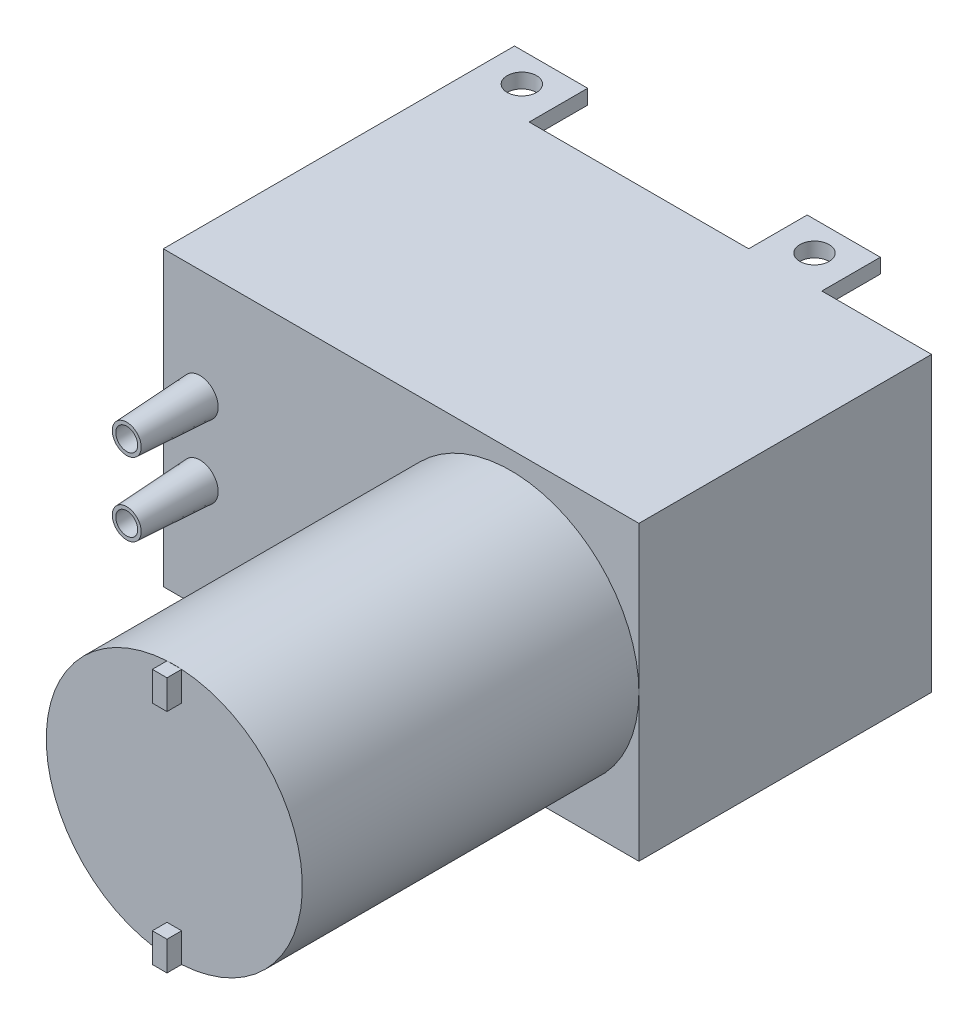
SolidWorks part; units mm, degrees
ref_plane "Plan de face" through (0, 0, 0) normal (0, 0, 1) x (1, 0, 0)
ref_plane "Plan de dessus" through (0, 0, 0) normal (0, 1, 0) x (1, 0, 0)
ref_plane "Plan de droite" through (0, 0, 0) normal (1, 0, 0) x (0, 0, -1)
sketch "Esquisse1" plane through (0, 0, 0) normal (0, 1, 0) x (1, 0, 0)
  line L1 (0, 0) -> (65, 0)
  line L2 (0, 0) -> (0, 40)
  line L3 (0, 40) -> (65, 40)
  line L4 (65, 0) -> (65, 40)
  dimension "D1" = 40
  dimension "D2" = 65
extrude "Boss.-Extru.1" add sketch "Esquisse1" along normal blind 40
sketch "Esquisse2" plane through (0, 0, 0) normal (0, 1, 0) x (1, 0, 0)
  text T0 "Pompe à air"
extrude "Enlèv. mat.-Extru.1" cut sketch "Esquisse2" along normal blind 0.1
sketch "Esquisse3" plane through (0, 0, 0) normal (0, 0, 1) x (1, 0, 0)
  line L0 (47.5, 2.5) -> (47.5, 0) construction
  line L1 (0, 0) -> (65, 0) construction
  line L2 (47.5, 37.5) -> (47.5, 40) construction
  line L3 (0, 40) -> (65, 40) construction
  line L4 (65, 40) -> (65, 0) construction
  circle A0 centre (47.5, 20) radius 17.5
  dimension "D1" = 35
extrude "Boss.-Extru.2" add sketch "Esquisse3" along normal blind 46
sketch "Esquisse4" plane through (0, 0, 46) normal (0, 0, 1) x (1, 0, 0)
  line L0 (65, 20) -> (30, 20) construction
  line L1 (48.5, 2.5286) -> (46.5, 2.5286)
  line L2 (48.5, 2.5286) -> (48.5, 6.5286)
  line L3 (48.5, 6.5286) -> (46.5, 6.5286)
  line L4 (46.5, 2.5286) -> (46.5, 6.5286)
  line L9 (48.5, 33.4714) -> (46.5, 33.4714)
  line L10 (46.5, 37.4714) -> (46.5, 33.4714)
  line L11 (48.5, 37.4714) -> (46.5, 37.4714)
  line L12 (48.5, 37.4714) -> (48.5, 33.4714)
  circle A1 centre (47.5, 20) radius 17.5 construction
  dimension "D1" = 4
  dimension "D2" = 2
extrude "Boss.-Extru.3" add sketch "Esquisse4" along normal blind 2
sketch "Esquisse5" plane through (0, 0, 0) normal (0, 0, 1) x (1, 0, 0)
  line L0 (0, 0) -> (65, 0) construction
  line L1 (0, 40) -> (0, 0) construction
  circle A0 centre (5, 15) radius 2.5
  circle A1 centre (5, 25) radius 2.5
  dimension "D4" = 5
  dimension "D5" = 5
  dimension "D1" = 15
  dimension "D2" = 25
  dimension "D3" = 5
extrude "Boss.-Extru.4" add sketch "Esquisse5" along normal blind 10 draft 3
sketch "Esquisse6" plane through (0, 0, 10) normal (0, 0, 1) x (1, 0, 0)
  circle A0 centre (5, 15) radius 1.5
  circle A1 centre (5, 25) radius 1.5
  dimension "D1" = 3
  dimension "D2" = 3
extrude "Enlèv. mat.-Extru.2" cut sketch "Esquisse6" against normal blind 10
sketch "Esquisse7" plane through (0, 0, -40) normal (0, 0, -1) x (-1, 0, 0)
  line L0 (-65, 40) -> (0, 40) construction
  line L1 (0, 40) -> (-10, 40)
  line L2 (0, 40) -> (0, 38)
  line L3 (0, 38) -> (-10, 38)
  line L4 (-10, 40) -> (-10, 38)
  line L5 (0, 40) -> (0, 0) construction
  line L6 (-40, 40) -> (-50, 40)
  line L7 (-40, 40) -> (-40, 38)
  line L8 (-40, 38) -> (-50, 38)
  line L9 (-50, 40) -> (-50, 38)
  dimension "D1" = 10
  dimension "D2" = 2
  dimension "D3" = 0
  dimension "D4" = 50
  dimension "D5" = 10
  dimension "D6" = 2
extrude "Boss.-Extru.5" add sketch "Esquisse7" along normal blind 8
sketch "Esquisse8" plane through (0, 38, 0) normal (0, -1, 0) x (-1, 0, 0)
  line L0 (-45, 48) -> (-45, 40) construction
  line L1 (-50, 48) -> (-40, 48) construction
  line L2 (-50, 40) -> (-40, 40) construction
  line L3 (-5, 48) -> (-5, 40) construction
  line L4 (-10, 48) -> (0, 48) construction
  line L5 (-10, 40) -> (0, 40) construction
  circle A0 centre (-45, 44) radius 2
  circle A1 centre (-5, 44) radius 2
  dimension "D1" = 4
  dimension "D2" = 4
extrude "Enlèv. mat.-Extru.3" cut sketch "Esquisse8" against normal through all
